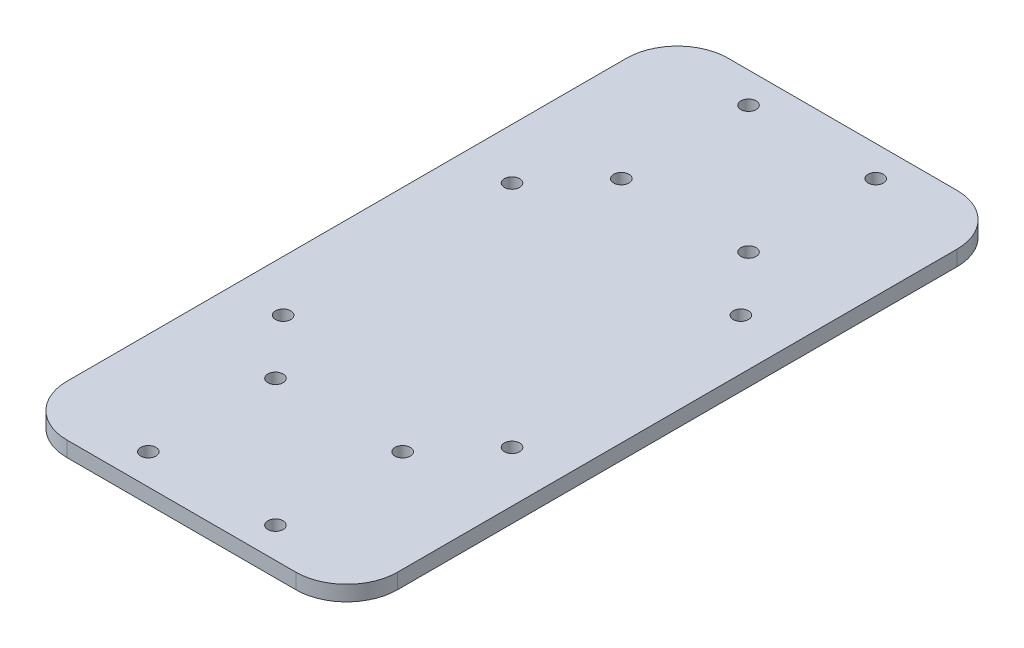
SolidWorks part; units mm, degrees
material "Thornel VCB-20 Carbon Cloth"
ref_plane "Front Plane" through (0, 0, 0) normal (0, 0, 1) x (1, 0, 0)
ref_plane "Top Plane" through (0, 0, 0) normal (0, 1, 0) x (1, 0, 0)
ref_plane "Right Plane" through (0, 0, 0) normal (1, 0, 0) x (0, 0, -1)
sketch "Sketch1" plane through (0, 0, 0) normal (0, 1, 0) x (1, 0, 0)
  line L0 (-32.5, 0) -> (32.5, 0) construction
  line L1 (32.5, -65) -> (32.5, 65)
  line L2 (32.5, 65) -> (-32.5, 65)
  line L3 (-32.5, 65) -> (-32.5, -65)
  line L4 (-22.5, 22.5) -> (22.5, 22.5) construction
  line L5 (32.5, -65) -> (-32.5, -65)
  circle A0 centre (-22.5, 22.5) radius 1.5
  circle A1 centre (22.5, 22.5) radius 1.5
  circle A2 centre (-22.5, -22.5) radius 1.5
  circle A3 centre (22.5, -22.5) radius 1.5
  point P5 (0, 0)
  point P10 (0, 22.5)
  dimension "D4" = 3
  dimension "D1" = 65
  dimension "D2" = 65
  dimension "D3" = 45
  dimension "D5" = 22.5
extrude "Boss-Extrude1" add sketch "Sketch1" along normal blind 3
sketch "Sketch2" plane through (0, 0, 0) normal (0, 1, 0) x (1, 0, 0)
  line L0 (-32.5, -65) -> (32.5, -65) construction
  line L1 (32.5, -65) -> (32.5, 65) construction
  line L2 (-32.5, 65) -> (-32.5, -65) construction
  line L3 (32.5, 65) -> (-32.5, 65) construction
  line L4 (-32.5, -65) -> (32.5, -65) construction
  line L5 (32.5, -65) -> (32.5, 65) construction
  line L6 (-32.5, 65) -> (-32.5, -65) construction
  line L7 (32.5, 65) -> (-32.5, 65) construction
  line L8 (-32.5, 0) -> (32.5, 0) construction
  line L9 (-32.5, 28) -> (32.5, 28) construction
  line L10 (0, 28) -> (0, 65) construction
  line L11 (-12.5, 34) -> (-12.5, 59) construction
  line L12 (-12.5, 59) -> (12.5, 59) construction
  line L13 (12.5, 59) -> (12.5, 34) construction
  line L14 (12.5, 34) -> (-12.5, 34) construction
  circle A0 centre (-12.5, 59) radius 1.5
  circle A1 centre (12.5, 59) radius 1.5
  circle A2 centre (12.5, 34) radius 1.5
  circle A3 centre (-12.5, 34) radius 1.5
  point P18 (0, 59)
  point P19 (0, 46.5)
  point P20 (-12.5, 46.5)
  dimension "D2" = 3
  dimension "D1" = 28
  dimension "D3" = 25
extrude "Cut-Extrude2" cut sketch "Sketch2" along normal through all
mirror "Mirror1" about plane through (0, 0, 0) normal (0, 0, 1) of "Cut-Extrude2"
fillet "Fillet1" radius 10 4 edges at (32.5, 1.5, -65) (-32.5, 1.5, -65) (-32.5, 1.5, 65) (32.5, 1.5, 65)
